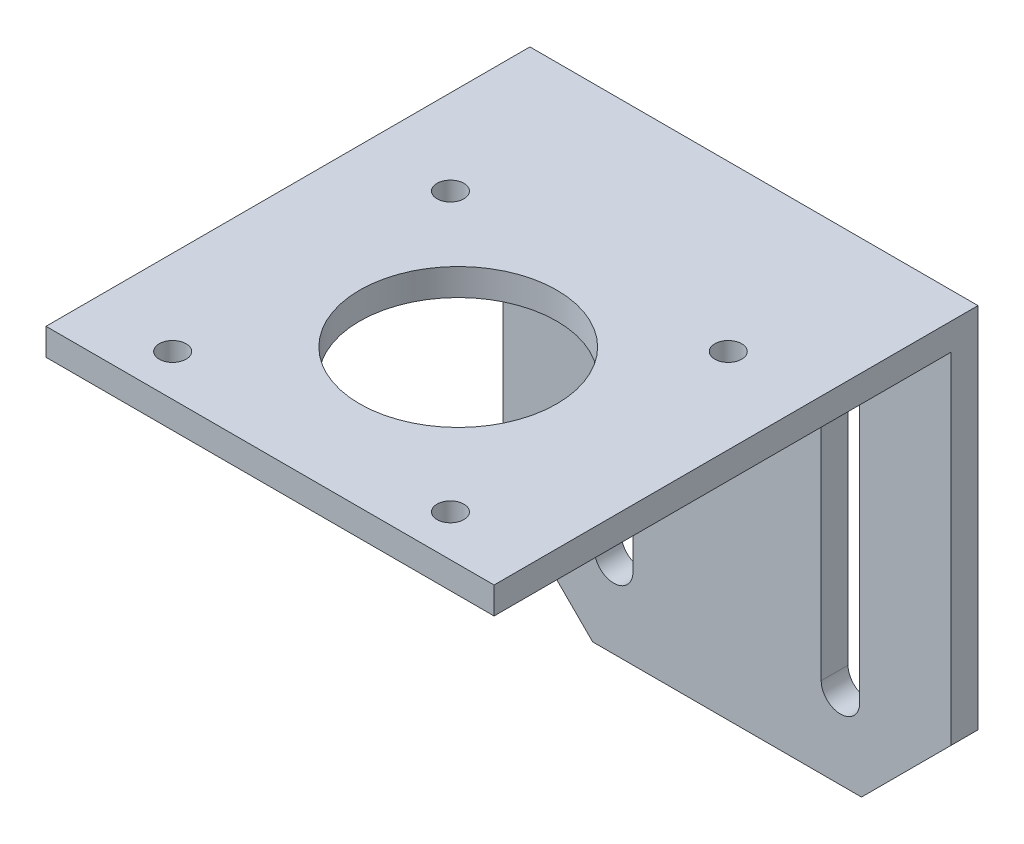
SolidWorks part; units mm, degrees
ref_plane "Front Plane" through (0, 0, 0) normal (0, 0, 1) x (1, 0, 0)
ref_plane "Top Plane" through (0, 0, 0) normal (0, 1, 0) x (1, 0, 0)
ref_plane "Right Plane" through (0, 0, 0) normal (1, 0, 0) x (0, 0, -1)
sketch "Sketch1" plane through (0, 0, 0) normal (0, 0, 1) x (1, 0, 0)
  line L0 (0, 25.5) -> (0, -25.5) construction
  line L1 (25, -25.5) -> (-25, -25.5)
  line L2 (25, -25.5) -> (25, 25.5)
  line L3 (25, 25.5) -> (-25, 25.5)
  line L4 (-25, -25.5) -> (-25, 25.5)
  line L5 (25, -25.5) -> (-25, 25.5) construction
  line L6 (25, 25.5) -> (-25, -25.5) construction
  line L7 (-10.5, 17.5) -> (-10.5, -16.5)
  line L8 (-14.8, 17.5) -> (-14.8, -16.5)
  line L9 (10.5, 17.5) -> (10.5, -16.5)
  line L10 (14.8, 17.5) -> (14.8, -16.5)
  arc A0 (-14.8, -16.5) -> (-10.5, -16.5) centre (-12.65, -16.5) ccw
  arc A1 (-10.5, 17.5) -> (-14.8, 17.5) centre (-12.65, 17.5) ccw
  arc A2 (14.8, -16.5) -> (10.5, -16.5) centre (12.65, -16.5) cw
  arc A3 (10.5, 17.5) -> (14.8, 17.5) centre (12.65, 17.5) cw
  point P0 (0, 0)
  dimension "D1" = 50
  dimension "D2" = 51
  dimension "D3" = 9
  dimension "D4" = 34
  dimension "D5" = 4.3
  dimension "D6" = 25.3
extrude "Boss-Extrude1" add sketch "Sketch1" along normal blind 3
sketch "Sketch3" plane through (0, 0, 0) normal (0, 0, -1) x (-1, 0, 0)
  line L0 (-25, -15.5) -> (-15, -25.5)
  line L1 (-25, -25.5) -> (-25, 25.5) construction
  line L2 (25, -25.5) -> (-25, -25.5) construction
  line L3 (15, -25.5) -> (25, -15.5)
  line L4 (25, 25.5) -> (25, -25.5) construction
  dimension "D1" = 10
  dimension "D2" = 10
  dimension "D3" = 10
  dimension "D4" = 10
extrude "Cut-Extrude-Thin1" cut sketch "Sketch3" against normal blind 3 thin
sketch "Sketch4" plane through (0, 0, 3) normal (0, 0, 1) x (1, 0, 0)
  line L1 (25, 22.5) -> (-25, 22.5)
  line L2 (25, 22.5) -> (25, 25.5)
  line L3 (25, 25.5) -> (-25, 25.5)
  line L4 (-25, 22.5) -> (-25, 25.5)
  line L5 (25, 22.5) -> (-25, 25.5) construction
  line L6 (25, 25.5) -> (-25, 22.5) construction
  point P0 (0, 24)
  dimension "D1" = 3
extrude "Boss-Extrude2" add sketch "Sketch4" along normal blind 51
sketch "Sketch5" plane through (0, 22.5, 0) normal (0, -1, 0) x (1, 0, 0)
  line L0 (0, 54) -> (0, 33) construction
  line L3 (-25, 54) -> (25, 54) construction
  circle A0 centre (0, 33) radius 11
  dimension "D2" = 22
  dimension "D1" = 21
extrude "Cut-Extrude1" cut sketch "Sketch5" against normal through all
sketch "Sketch6" plane through (0, 22.5, 0) normal (0, -1, 0) x (1, 0, 0)
  circle A0 centre (-15.5, 49.3672) radius 1.5
  circle A1 centre (-15.5, 18.3672) radius 1.5
  circle A2 centre (15.5, 18.3672) radius 1.5
  circle A3 centre (15.5, 49.3672) radius 1.5
  dimension "D1" = 3
  dimension "D3" = 3
  dimension "D4" = 31
extrude "Cut-Extrude2" cut sketch "Sketch6" against normal through all and the other way through all
